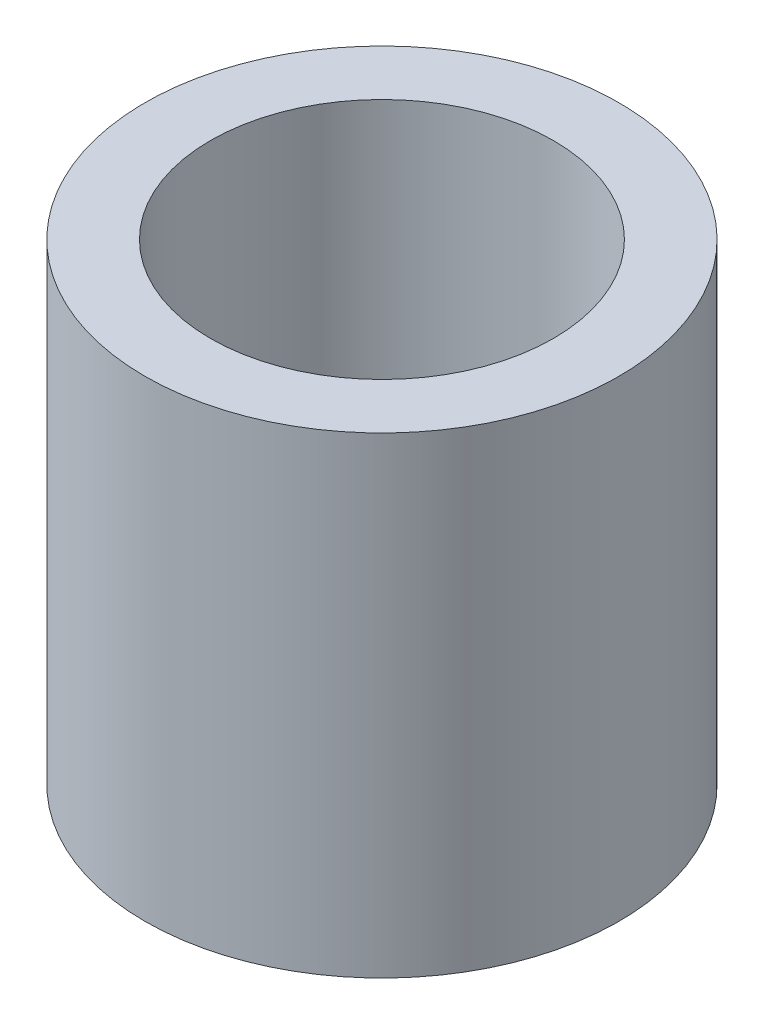
SolidWorks part; units mm, degrees
ref_plane "Front Plane" through (0, 0, 0) normal (0, 0, 1) x (1, 0, 0)
ref_plane "Top Plane" through (0, 0, 0) normal (0, 1, 0) x (1, 0, 0)
ref_plane "Right Plane" through (0, 0, 0) normal (1, 0, 0) x (0, 0, -1)
sketch "Sketch1" plane through (0, 0, 0) normal (0, 1, 0) x (1, 0, 0)
  circle A0 centre (0, 0) radius 12.3
  dimension "D1" = 24.6
extrude "Boss-Extrude1" add sketch "Sketch1" along normal blind 24.5
sketch "Sketch2" plane through (0, 24.5, 0) normal (0, 1, 0) x (1, 0, 0)
  circle A0 centre (0, 0) radius 8.9
  circle A1 centre (0, 0) radius 12.3 construction
  dimension "D1" = 3.4
extrude "Cut-Extrude1" cut sketch "Sketch2" against normal blind 20
sketch "Sketch3" plane through (0, 0, 0) normal (0, -1, 0) x (1, 0, 0)
  circle A0 centre (0, 0) radius 7.4
  dimension "D1" = 14.8
extrude "Cut-Extrude2" cut sketch "Sketch3" against normal blind 1
sketch "Sketch4" plane through (0, 1, 0) normal (0, -1, 0) x (1, 0, 0)
  circle A0 centre (0, 0) radius 4.5
  dimension "D1" = 9
extrude "Cut-Extrude3" cut sketch "Sketch4" against normal through all
